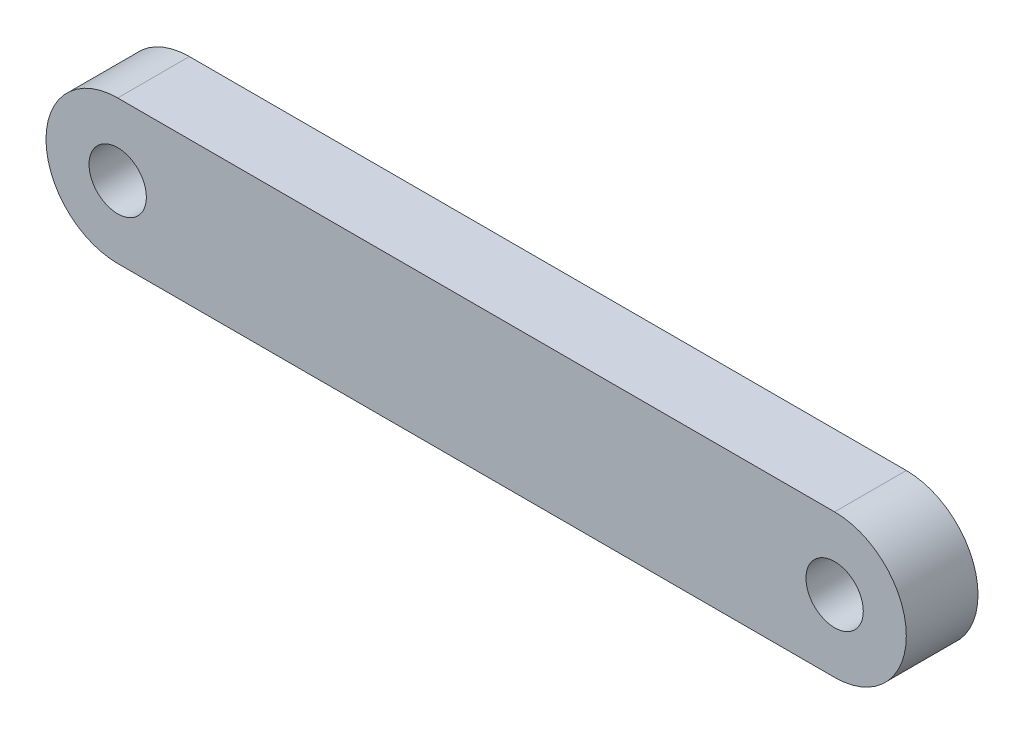
SolidWorks part; units mm, degrees
ref_plane "Plan de face" through (0, 0, 0) normal (0, 0, 1) x (1, 0, 0)
ref_plane "Plan de dessus" through (0, 0, 0) normal (0, 1, 0) x (1, 0, 0)
ref_plane "Plan de droite" through (0, 0, 0) normal (1, 0, 0) x (0, 0, -1)
sketch "Esquisse1" plane through (0, 0, 0) normal (0, 0, 1) x (1, 0, 0)
  line L0 (0, 0) -> (50, 0) construction
  line L1 (0, 5) -> (50, 5)
  line L2 (0, -5) -> (50, -5)
  arc A0 (0, 5) -> (0, -5) centre (0, 0) ccw
  arc A1 (50, -5) -> (50, 5) centre (50, 0) ccw
  circle A2 centre (0, 0) radius 2
  circle A3 centre (50, 0) radius 2
  point P3 (25, 0)
  dimension "D2" = 5
  dimension "D3" = 4
  dimension "D4" = 4
  dimension "D1" = 50
extrude "Boss.-Extru.1" add sketch "Esquisse1" along normal blind 5
